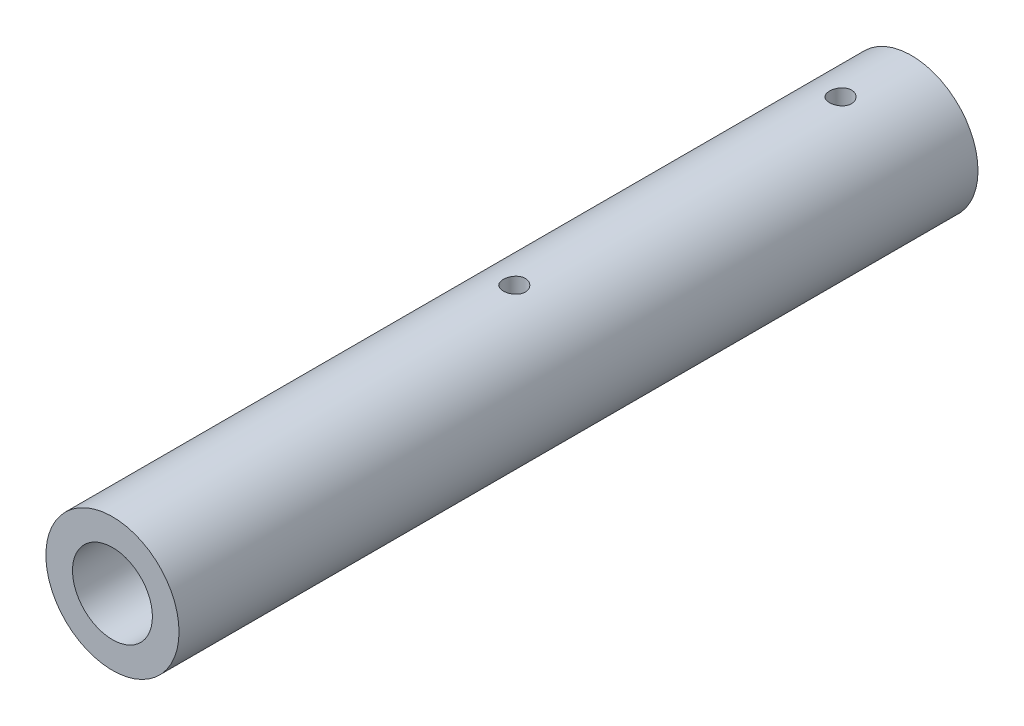
SolidWorks part; units mm, degrees
ref_plane "Спереди" through (0, 0, 0) normal (0, 0, 1) x (1, 0, 0)
ref_plane "Сверху" through (0, 0, 0) normal (0, 1, 0) x (1, 0, 0)
ref_plane "Справа" through (0, 0, 0) normal (1, 0, 0) x (0, 0, -1)
sketch "Эскиз1" plane through (0, 0, 0) normal (0, 0, 1) x (1, 0, 0)
  circle A0 centre (0, 0) radius 10
  circle A1 centre (0, 0) radius 6
  dimension "D1" = 12
  dimension "D2" = 20
extrude "Бобышка-Вытянуть1" add sketch "Эскиз1" along normal blind 120
sketch "Эскиз2" plane through (0, 0, 0) normal (0, 1, 0) x (1, 0, 0)
  line L1 (10, 0) -> (-10, 0) construction
  line L3 (6, 0) -> (-6, 0) construction
  circle A0 centre (0, -10.65) radius 1.65
  circle A1 centre (0, -59.65) radius 1.65
  dimension "D1" = 3.3
  dimension "D2" = 9
  dimension "D3" = 58
extrude "Вырез-Вытянуть1" cut sketch "Эскиз2" against normal through all both and the other way through all
